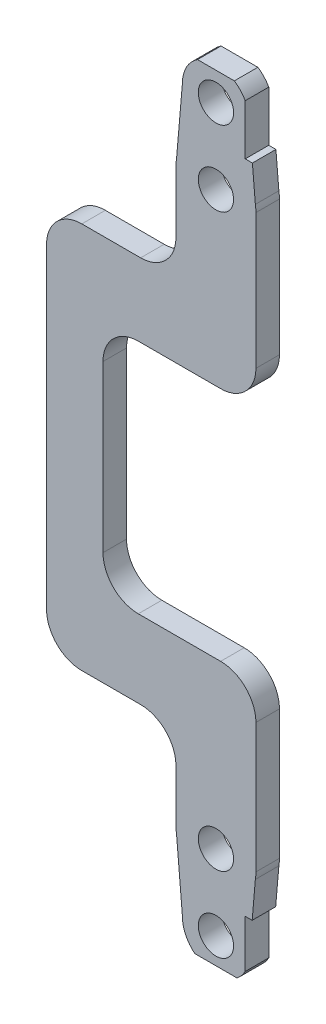
SolidWorks part; units mm, degrees
ref_plane "Спереди" through (0, 0, 0) normal (0, 0, 1) x (1, 0, 0)
ref_plane "Сверху" through (0, 0, 0) normal (0, 1, 0) x (1, 0, 0)
ref_plane "Справа" through (0, 0, 0) normal (1, 0, 0) x (0, 0, -1)
sketch "Skizze1" plane through (0, 0, 0) normal (0, 0, 1) x (1, 0, 0)
  circle A4 centre (-44.1261, -31.0496) radius 2.85
  circle A5 centre (-44.1261, -24.6496) radius 3.4
  circle A6 centre (-44.1261, 23.8904) radius 3.4
  circle A7 centre (-44.1261, 30.2904) radius 2.85
sketch "Skizze5" plane through (0, 0, 0) normal (0, 0, 1) x (1, 0, 0)
  line L0 (-41.2761, 30.2904) -> (-40.7261, 23.8904)
  line L1 (-40.7261, 23.8904) -> (-40.7261, -24.6496)
  line L2 (-40.7261, -24.6496) -> (-41.2761, -31.0496)
  line L3 (-46.9761, -31.0496) -> (-47.5261, -24.6496)
  line L4 (-47.5261, -24.6496) -> (-47.5261, 23.8904)
  line L5 (-47.5261, 23.8904) -> (-46.9761, 30.2904)
  circle A0 centre (-44.1261, -31.0496) radius 2.85 construction
  circle A1 centre (-44.1261, -24.6496) radius 3.4 construction
  circle A2 centre (-44.1261, 23.8904) radius 3.4 construction
  circle A3 centre (-44.1261, 30.2904) radius 2.85 construction
  circle A4 centre (-44.1261, -31.0496) radius 2.85
  circle A5 centre (-44.1261, -24.6496) radius 3.4
  circle A6 centre (-44.1261, 23.8904) radius 3.4
  circle A7 centre (-44.1261, 30.2904) radius 2.85
extrude "Aufsatz-Linear austragen2" add sketch "Skizze5" along normal blind 2 contours A6 L4 A5 L1 | L0 A6 L5 | A7 | A7 L5 A6 L0 | L2 A5 L3 | A5 L3 A4 L2 | A4
sketch "Skizze7" plane through (0, 0, 0) normal (0, 0, -1) x (-1, 0, 0)
  circle A0 centre (44.1261, 30.2904) radius 1.5
  circle A1 centre (44.1261, 23.8904) radius 2.5
  circle A2 centre (44.1261, -24.6496) radius 2.5
  circle A3 centre (44.1261, -31.0496) radius 1.5
  dimension "D1" = 5
  dimension "D2" = 3
  dimension "D3" = 5
  dimension "D4" = 3
extrude "Schnitt-Linear austragen1" cut sketch "Skizze7" against normal blind 2
sketch "Skizze8" plane through (0, 0, 0) normal (0, 0, -1) x (-1, 0, 0)
  line L0 (47.5261, -24.6496) -> (47.5261, 23.8904) construction
  line L1 (47.5261, 15.6589) -> (58.5261, 15.6589)
  line L2 (47.5261, 15.6589) -> (47.5261, -17.2321)
  line L3 (47.5261, -17.2321) -> (58.5261, -17.2321)
  line L4 (58.5261, 15.6589) -> (58.5261, -17.2321)
  dimension "D1" = 11
extrude "Aufsatz-Linear austragen3" add sketch "Skizze8" against normal blind 2
sketch "Skizze9" plane through (0, 0, 0) normal (0, 0, -1) x (-1, 0, 0)
  line L0 (40.7261, 23.8904) -> (40.7261, -24.6496) construction
  line L1 (40.7261, 9.4256) -> (53.7261, 9.4256)
  line L2 (40.7261, 9.4256) -> (40.7261, -10.647)
  line L3 (40.7261, -10.647) -> (53.7261, -10.647)
  line L4 (53.7261, 9.4256) -> (53.7261, -10.647)
  dimension "D1" = 13
extrude "Schnitt-Linear austragen2" cut sketch "Skizze9" against normal blind 2
sketch "Skizze10" plane through (0, 0, 0) normal (0, 0, -1) x (-1, 0, 0)
  circle A0 centre (44.1261, 23.8904) radius 3.4
  circle A1 centre (44.1261, -24.6496) radius 3.4
extrude "Aufsatz-Linear austragen4" add sketch "Skizze10" against normal blind 2
sketch "Skizze11" plane through (0, 0, 0) normal (0, 0, -1) x (-1, 0, 0)
  circle A0 centre (44.1261, -24.6496) radius 1.5
  circle A1 centre (44.1261, 23.8904) radius 1.5
  dimension "D1" = 3
extrude "Schnitt-Linear austragen3" cut sketch "Skizze11" against normal blind 5
fillet "Verrundung3" radius 3 2 edges at (-53.7261, 9.4256, 1) (-40.7261, 9.4256, 1)
fillet "Verrundung4" radius 3 2 edges at (-40.7261, -10.647, 1) (-53.7261, -10.647, 1)
fillet "Verrundung5" radius 3 2 edges at (-47.5261, -17.2321, 1) (-58.5261, -17.2321, 1)
fillet "Verrundung6" radius 3 2 edges at (-47.5261, 15.6589, 1) (-58.5261, 15.6589, 1)
sketch "Skizze12" plane through (0, 0, 0) normal (0, 0, -1) x (-1, 0, 0)
  line L1 (41.7363, 34.3959) -> (46.2941, 34.3959)
  line L2 (41.7363, 34.3959) -> (41.7363, 32.6714)
  line L3 (41.7363, 32.6714) -> (46.2941, 32.6714)
  line L4 (46.2941, 34.3959) -> (46.2941, 32.6714)
  line L5 (48.101, -34.5591) -> (40.2819, -34.5591)
  line L6 (48.101, -34.5591) -> (48.101, -33.264)
  line L7 (48.101, -33.264) -> (40.2819, -33.264)
  line L8 (40.2819, -34.5591) -> (40.2819, -33.264)
  line L9 (41.6346, 32.4756) -> (39.8789, 32.4756)
  line L10 (41.6346, 32.4756) -> (41.6346, 27.3908)
  line L11 (41.6346, 27.3908) -> (39.8789, 27.3908)
  line L12 (39.8789, 32.4756) -> (39.8789, 27.3908)
  line L13 (39.8789, -32.8982) -> (41.6346, -32.8982)
  line L14 (39.8789, -32.8982) -> (39.8789, -28.3735)
  line L15 (39.8789, -28.3735) -> (41.6346, -28.3735)
  line L16 (41.6346, -32.8982) -> (41.6346, -28.3735)
extrude "Schnitt-Linear austragen4" cut sketch "Skizze12" against normal blind 10
